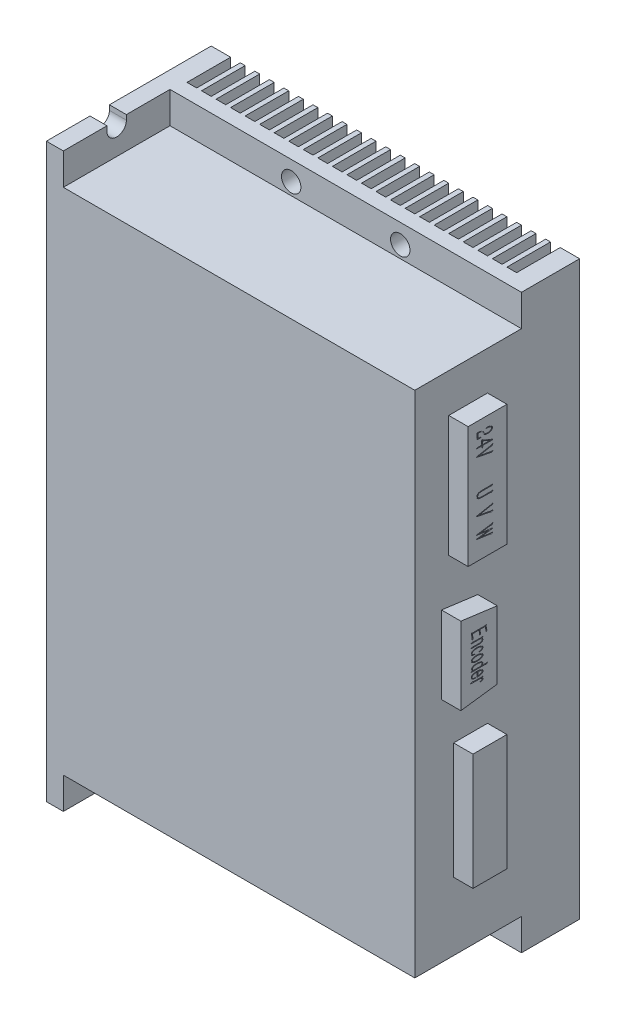
SolidWorks part; units mm, degrees
ref_plane "前视基准面" through (0, 0, 0) normal (0, 0, 1) x (1, 0, 0)
ref_plane "上视基准面" through (0, 0, 0) normal (0, 1, 0) x (1, 0, 0)
ref_plane "右视基准面" through (0, 0, 0) normal (1, 0, 0) x (0, 0, -1)
sketch "草图1" plane through (0, 0, 0) normal (0, 0, 1) x (1, 0, 0)
  line L1 (38, -59) -> (-38, -59)
  line L2 (38, -59) -> (38, 59)
  line L3 (38, 59) -> (-38, 59)
  line L4 (-38, -59) -> (-38, 59)
  line L5 (38, -59) -> (-38, 59) construction
  line L6 (38, 59) -> (-38, -59) construction
  point P0 (0, 0)
  dimension "D1" = 76
  dimension "D2" = 118
extrude "凸台-拉伸1" add sketch "草图1" along normal blind 34
sketch "草图2" plane through (0, 0, 34) normal (0, 0, 1) x (1, 0, 0)
  line L0 (0, 0) -> (-38, 0) construction
  line L1 (38, 52.5) -> (-34.5, 52.5)
  line L2 (38, -52.5) -> (38, -59)
  line L3 (38, -52.5) -> (-34.5, -52.5)
  line L4 (-34.5, 52.5) -> (-34.5, -52.5) construction
  line L5 (-38, 59) -> (-38, -59) construction
  line L7 (38, -59) -> (-34.5, -59)
  line L8 (-38, -59) -> (38, -59) construction
  line L9 (-34.5, -59) -> (-34.5, -52.5)
  line L10 (38, 52.5) -> (38, 59)
  line L11 (38, 59) -> (-34.5, 59)
  line L12 (38, 59) -> (-38, 59) construction
  line L13 (-34.5, 59) -> (-34.5, 52.5)
  dimension "D1" = 105
  dimension "D2" = 3.5
extrude "切除-拉伸1" cut sketch "草图2" against normal offset from surface (22 mm away) 12 up to face at (0, 0, 0)
sketch "草图3" plane through (0, 59, 0) normal (0, 1, 0) x (1, 0, 0)
  line L0 (38, 0) -> (-38, 0) construction
  line L1 (-34, 0) -> (-32, 0)
  line L2 (-34, 0) -> (-34, -9)
  line L3 (-34, -9) -> (-32, -9)
  line L4 (-32, 0) -> (-32, -9)
  line L5 (-38, -34) -> (-38, 0) construction
  line L6 (-29, 0) -> (-29, -9)
  line L7 (-31, 0) -> (-31, -9)
  line L8 (-31, 0) -> (-29, 0)
  line L9 (-31, -9) -> (-29, -9)
  line L10 (-26, 0) -> (-26, -9)
  line L11 (-28, 0) -> (-28, -9)
  line L12 (-28, 0) -> (-26, 0)
  line L13 (-28, -9) -> (-26, -9)
  line L14 (-23, 0) -> (-23, -9)
  line L15 (-25, 0) -> (-25, -9)
  line L16 (-25, 0) -> (-23, 0)
  line L17 (-25, -9) -> (-23, -9)
  line L18 (-20, 0) -> (-20, -9)
  line L19 (-22, 0) -> (-22, -9)
  line L20 (-22, 0) -> (-20, 0)
  line L21 (-22, -9) -> (-20, -9)
  line L22 (-17, 0) -> (-17, -9)
  line L23 (-19, 0) -> (-19, -9)
  line L24 (-19, 0) -> (-17, 0)
  line L25 (-19, -9) -> (-17, -9)
  line L26 (-14, 0) -> (-14, -9)
  line L27 (-16, 0) -> (-16, -9)
  line L28 (-16, 0) -> (-14, 0)
  line L29 (-16, -9) -> (-14, -9)
  line L30 (-11, 0) -> (-11, -9)
  line L31 (-13, 0) -> (-13, -9)
  line L32 (-13, 0) -> (-11, 0)
  line L33 (-13, -9) -> (-11, -9)
  line L34 (-8, 0) -> (-8, -9)
  line L35 (-10, 0) -> (-10, -9)
  line L36 (-10, 0) -> (-8, 0)
  line L37 (-10, -9) -> (-8, -9)
  line L38 (-5, 0) -> (-5, -9)
  line L39 (-7, 0) -> (-7, -9)
  line L40 (-7, 0) -> (-5, 0)
  line L41 (-7, -9) -> (-5, -9)
  line L42 (-2, 0) -> (-2, -9)
  line L43 (-4, 0) -> (-4, -9)
  line L44 (-4, 0) -> (-2, 0)
  line L45 (-4, -9) -> (-2, -9)
  line L46 (1, 0) -> (1, -9)
  line L47 (-1, 0) -> (-1, -9)
  line L48 (-1, 0) -> (1, 0)
  line L49 (-1, -9) -> (1, -9)
  line L50 (4, 0) -> (4, -9)
  line L51 (2, 0) -> (2, -9)
  line L52 (2, 0) -> (4, 0)
  line L53 (2, -9) -> (4, -9)
  line L54 (7, 0) -> (7, -9)
  line L55 (5, 0) -> (5, -9)
  line L56 (5, 0) -> (7, 0)
  line L57 (5, -9) -> (7, -9)
  line L58 (10, 0) -> (10, -9)
  line L59 (8, 0) -> (8, -9)
  line L60 (8, 0) -> (10, 0)
  line L61 (8, -9) -> (10, -9)
  line L62 (13, 0) -> (13, -9)
  line L63 (11, 0) -> (11, -9)
  line L64 (11, 0) -> (13, 0)
  line L65 (11, -9) -> (13, -9)
  line L66 (16, 0) -> (16, -9)
  line L67 (14, 0) -> (14, -9)
  line L68 (14, 0) -> (16, 0)
  line L69 (14, -9) -> (16, -9)
  line L70 (19, 0) -> (19, -9)
  line L71 (17, 0) -> (17, -9)
  line L72 (17, 0) -> (19, 0)
  line L73 (17, -9) -> (19, -9)
  line L74 (22, 0) -> (22, -9)
  line L75 (20, 0) -> (20, -9)
  line L76 (20, 0) -> (22, 0)
  line L77 (20, -9) -> (22, -9)
  line L78 (25, 0) -> (25, -9)
  line L79 (23, 0) -> (23, -9)
  line L80 (23, 0) -> (25, 0)
  line L81 (23, -9) -> (25, -9)
  line L82 (28, 0) -> (28, -9)
  line L83 (26, 0) -> (26, -9)
  line L84 (26, 0) -> (28, 0)
  line L85 (26, -9) -> (28, -9)
  line L86 (31, 0) -> (31, -9)
  line L87 (29, 0) -> (29, -9)
  line L88 (29, 0) -> (31, 0)
  line L89 (29, -9) -> (31, -9)
  line L90 (34, 0) -> (34, -9)
  line L91 (32, 0) -> (32, -9)
  line L92 (32, 0) -> (34, 0)
  line L93 (32, -9) -> (34, -9)
  dimension "D1" = 9
  dimension "D2" = 4
  dimension "D3" = 2
  dimension "D4" = 23
extrude "切除-拉伸2" cut sketch "草图3" against normal through all
sketch "草图4" plane through (-34.5, 0, 0) normal (1, 0, 0) x (0, 0, -1)
  line L0 (-23, 60) -> (-23, 58) construction
  line L2 (-21, 60) -> (-21, 58)
  line L3 (-25, 60) -> (-25, 58)
  line L4 (-34, 59) -> (-34, 52.5) construction
  line L5 (-12, 59) -> (-34, 59) construction
  line L6 (0, 0) -> (-34, 0) construction
  line L7 (-34, -52.5) -> (-34, 52.5) construction
  line L8 (-23, -60) -> (-23, -58) construction
  line L9 (-21, -60) -> (-21, -58)
  line L10 (-25, -60) -> (-25, -58)
  arc A0 (-21, 60) -> (-25, 60) centre (-23, 60) ccw
  arc A1 (-25, 58) -> (-21, 58) centre (-23, 58) ccw
  arc A2 (-21, -60) -> (-25, -60) centre (-23, -60) cw
  arc A3 (-25, -58) -> (-21, -58) centre (-23, -58) cw
  point P4 (-23, 59)
  point P10 (-25, 59)
  point P19 (-23, -59)
  dimension "D2" = 2
  dimension "D1" = 9
  dimension "D3" = 2
extrude "切除-拉伸3" cut sketch "草图4" against normal through all
sketch "草图6" plane through (0, 0, 12) normal (0, 0, 1) x (1, 0, 0)
  line L0 (38, 59) -> (38, 52.5) construction
  line L2 (-34.5, 59) -> (38, 59) construction
  line L4 (0, 0) -> (18.7737, 0) construction
  circle A0 centre (-9.5, 55) radius 2
  circle A1 centre (13, 55) radius 2
  circle A2 centre (13, -55) radius 2
  circle A3 centre (-9.5, -55) radius 2
  dimension "D1" = 4
  dimension "D2" = 22.5
  dimension "D3" = 25
  dimension "D4" = 4
extrude "切除-拉伸4" cut sketch "草图6" against normal through all
sketch "草图7" plane through (38, 0, 0) normal (1, 0, 0) x (0, 0, -1)
  line L0 (-12, 52.5) -> (-12, 59) construction
  line L1 (-27, 44.5) -> (-19, 44.5)
  line L2 (-27, 44.5) -> (-27, 19.5)
  line L3 (-27, 19.5) -> (-19, 19.5)
  line L4 (-19, 44.5) -> (-19, 19.5)
  line L5 (-12, 52.5) -> (-34, 52.5) construction
  line L6 (-12, -52.5) -> (-34, -52.5) construction
  line L7 (-26, -14.5) -> (-19, -14.5)
  line L8 (-26, -14.5) -> (-26, -38.5)
  line L9 (-26, -38.5) -> (-19, -38.5)
  line L10 (-19, -14.5) -> (-19, -38.5)
  line L11 (-19, 19.5) -> (-19, -14.5) construction
  line L12 (-28.5, 10.5) -> (-21, 10.5) construction
  line L13 (-28.5, 10.5) -> (-28.5, -5.5)
  line L14 (-28.5, -5.5) -> (-21, -5.5) construction
  line L15 (-21, 9.5) -> (-21, -4.5)
  line L16 (-19, 2.5) -> (-33.1265, 2.5) construction
  line L17 (-28.5, 10.5) -> (-21, 9.5)
  line L18 (-28.5, -5.5) -> (-21, -4.5)
  dimension "D1" = 8
  dimension "D2" = 25
  dimension "D3" = 7
  dimension "D4" = 8
  dimension "D5" = 7
  dimension "D6" = 24
  dimension "D7" = 14
  dimension "D8" = 2
  dimension "D9" = 7.5
  dimension "D10" = 16
  dimension "D11" = 14
extrude "凸台-拉伸2" add sketch "草图7" along normal blind 4
sketch "草图8" plane through (0, -52.5, 0) normal (0, -1, 0) x (1, 0, 0)
  line L1 (9.4647, 20.3325) -> (-2.0878, 20.3325)
  line L2 (9.4647, 20.3325) -> (9.4647, 28.6858)
  line L3 (9.4647, 28.6858) -> (-2.0878, 28.6858)
  line L4 (-2.0878, 20.3325) -> (-2.0878, 28.6858)
  line L5 (9.4647, 20.3325) -> (-2.0878, 28.6858) construction
  line L6 (9.4647, 28.6858) -> (-2.0878, 20.3325) construction
  point P0 (3.6884, 24.5091)
extrude "切除-拉伸5" cut sketch "草图8" against normal blind 0.2
sketch "草图10" plane through (42, 0, 0) normal (1, 0, 0) x (0, 0, -1)
  line L0 (-25.4968, 44.5) -> (-25.4968, 19.5) construction
  line L1 (-19, 44.5) -> (-27, 44.5) construction
  line L2 (-27, 19.5) -> (-19, 19.5) construction
sketch "草图11" plane through (42, 0, 0) normal (1, 0, 0) x (0, 0, -1)
  text T0 " 24V   U V W"
extrude "切除-拉伸6" cut sketch "草图11" against normal blind 0.2
sketch "草图12" plane through (42, 0, 0) normal (1, 0, 0) x (0, 0, -1)
  line L0 (-26.6475, 10.253) -> (-26.6475, -5.253) construction
  line L1 (-21, 9.5) -> (-28.5, 10.5) construction
  line L2 (-28.5, -5.5) -> (-21, -4.5) construction
  text T0 "Encoder"
extrude "切除-拉伸7" cut sketch "草图12" against normal blind 0.2
